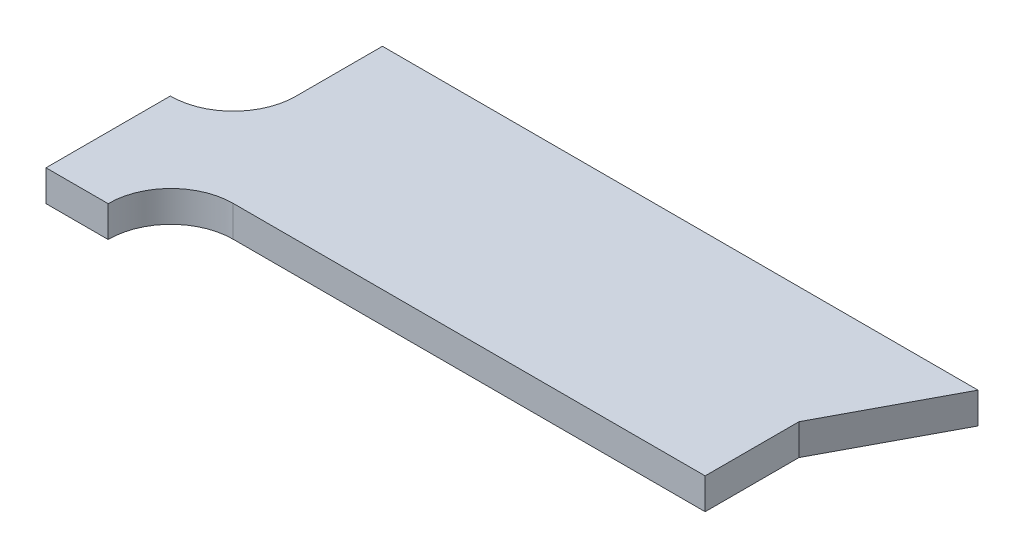
SolidWorks part; units mm, degrees
ref_plane "Front Plane" through (0, 0, 0) normal (0, 0, 1) x (1, 0, 0)
ref_plane "Top Plane" through (0, 0, 0) normal (0, 1, 0) x (1, 0, 0)
ref_plane "Right Plane" through (0, 0, 0) normal (1, 0, 0) x (0, 0, -1)
sketch "Sketch2" plane through (0, 0, 0) normal (0, 1, 0) x (1, 0, 0)
  line L0 (0, 0) -> (0.5, 0)
  line L1 (0, 0) -> (0, 1)
  line L2 (5.2981, 2.2) -> (4.7981, 1.2596)
  line L3 (0.5067, 1.5034) -> (0.5067, 2.2)
  line L4 (0.5067, 2.2) -> (5.2981, 2.2)
  line L5 (1, 0.5049) -> (4.7981, 0.5049)
  line L6 (4.7981, 0.5049) -> (4.7981, 1.2596)
  line L7 (0.25, 0) -> (0.25, 1.5) construction
  arc A0 (0.5, 0) -> (1, 0.5049) centre (1, 0.0049) cw
  arc A2 (0, 1) -> (0.5067, 1.5034) centre (0.0034, 1.5034) ccw
  dimension "D1" = 62
  dimension "D2" = 0.5
  dimension "D3" = 2.2
extrude "Boss-Extrude1" add sketch "Sketch2" along normal blind 0.25
